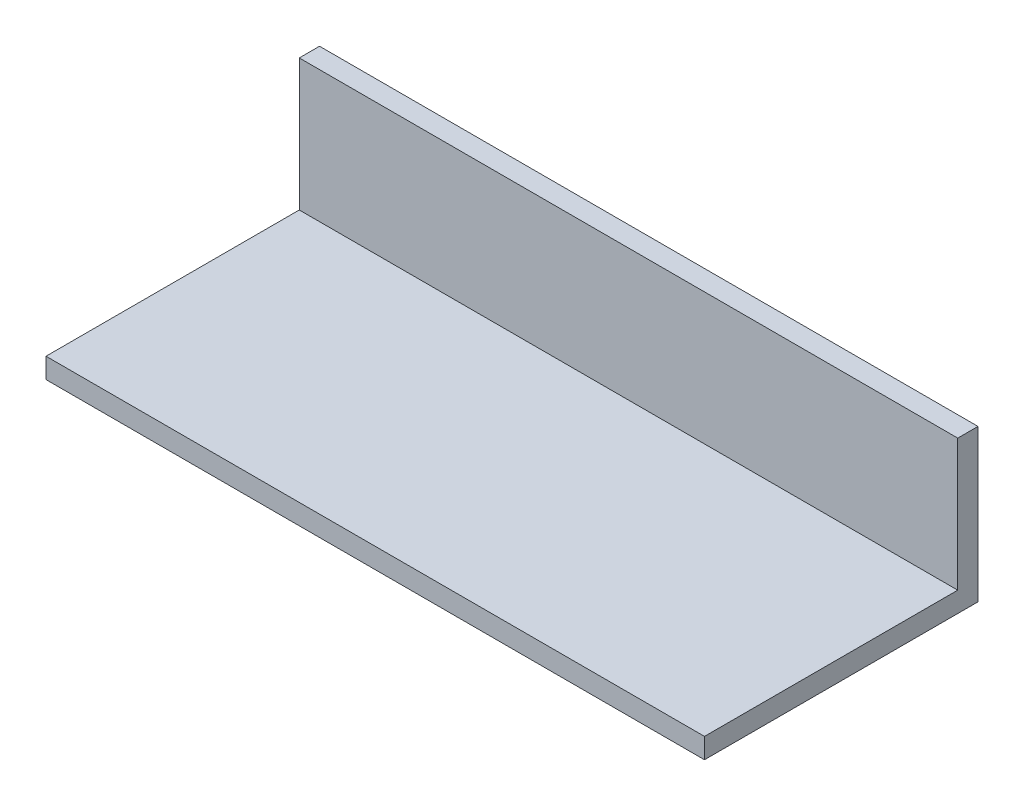
SolidWorks part; units mm, degrees
material "Plastique personnalisé"
ref_plane "Plan de face" through (0, 0, 0) normal (0, 0, 1) x (1, 0, 0)
ref_plane "Plan de dessus" through (0, 0, 0) normal (0, 1, 0) x (1, 0, 0)
ref_plane "Plan de droite" through (0, 0, 0) normal (1, 0, 0) x (0, 0, -1)
sketch "Esquisse1" plane through (0, 0, 0) normal (0, 1, 0) x (1, 0, 0)
  line L1 (-23.6607, 12.4554) -> (41.3393, 12.4554)
  line L2 (-23.6607, 12.4554) -> (-23.6607, -12.5446)
  line L3 (-23.6607, -12.5446) -> (41.3393, -12.5446)
  line L4 (41.3393, 12.4554) -> (41.3393, -12.5446)
  dimension "D1" = 65
  dimension "D2" = 25
extrude "Boss.-Extru.1" add sketch "Esquisse1" along normal blind 2 contours L1 L4 L3 L2
ref_plane "Plan1" through (0, 0, -12.4554) normal (0, 0, -1) x (-1, 0, 0)
sketch "Esquisse3" plane through (0, 0, -12.4554) normal (0, 0, -1) x (-1, 0, 0)
  line L0 (-41.3393, 2) -> (-41.3393, 0) construction
  line L1 (23.6607, 0) -> (-41.3393, 0)
  line L2 (23.6607, 0) -> (23.6607, 15)
  line L3 (23.6607, 15) -> (-41.3393, 15)
  line L4 (-41.3393, 0) -> (-41.3393, 15)
  dimension "D1" = 0
  dimension "D2" = 15
extrude "Boss.-Extru.2" add sketch "Esquisse3" along normal blind 2
